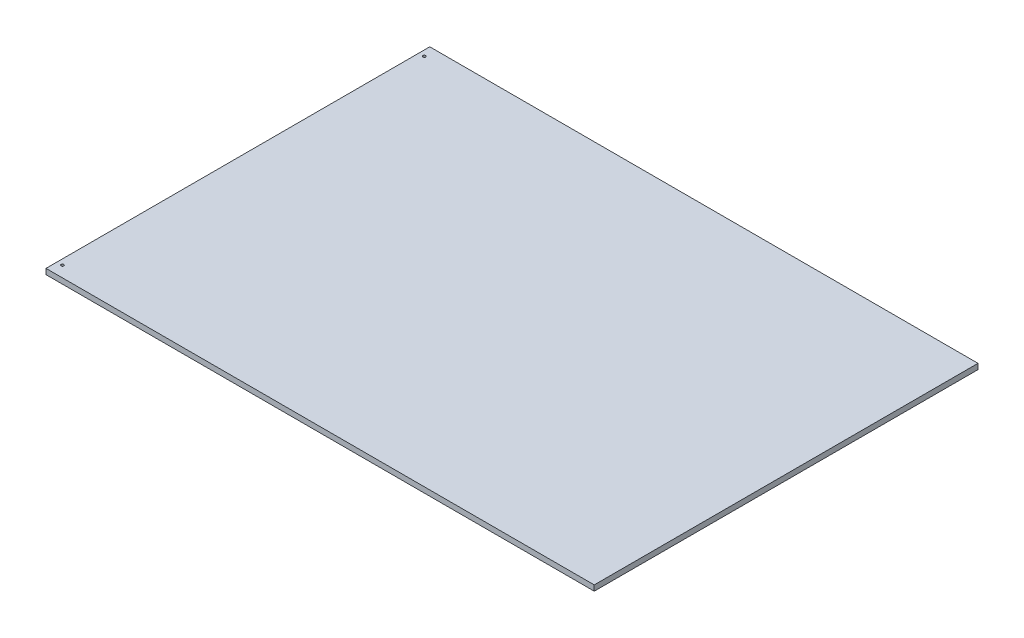
SolidWorks part; units mm, degrees
ref_plane "Front Plane" through (0, 0, 0) normal (0, 0, 1) x (1, 0, 0)
ref_plane "Top Plane" through (0, 0, 0) normal (0, 1, 0) x (1, 0, 0)
ref_plane "Right Plane" through (0, 0, 0) normal (1, 0, 0) x (0, 0, -1)
sketch "Sketch1" plane through (0, 0, 0) normal (0, 1, 0) x (1, 0, 0)
  line L1 (0, 0) -> (1270, 0)
  line L2 (0, 0) -> (0, 889)
  line L3 (0, 889) -> (1270, 889)
  line L4 (1270, 0) -> (1270, 889)
  dimension "D1" = 1270
  dimension "D2" = 889
extrude "Boss-Extrude1" add sketch "Sketch1" along normal blind 12.7
sketch "Sketch2" plane through (0, 12.7, 0) normal (0, 1, 0) x (1, 0, 0)
  line L0 (1270, 889) -> (0, 889) construction
  line L1 (0, 889) -> (0, 0) construction
  line L2 (0, 0) -> (1270, 0) construction
  circle A0 centre (12.7, 863.6) radius 3.175
  circle A1 centre (12.7, 25.4) radius 3.175
  dimension "D1" = 25.4
  dimension "D2" = 12.7
  dimension "D3" = 25.4
extrude "Cut-Extrude2" cut sketch "Sketch2" against normal blind 1222.502
